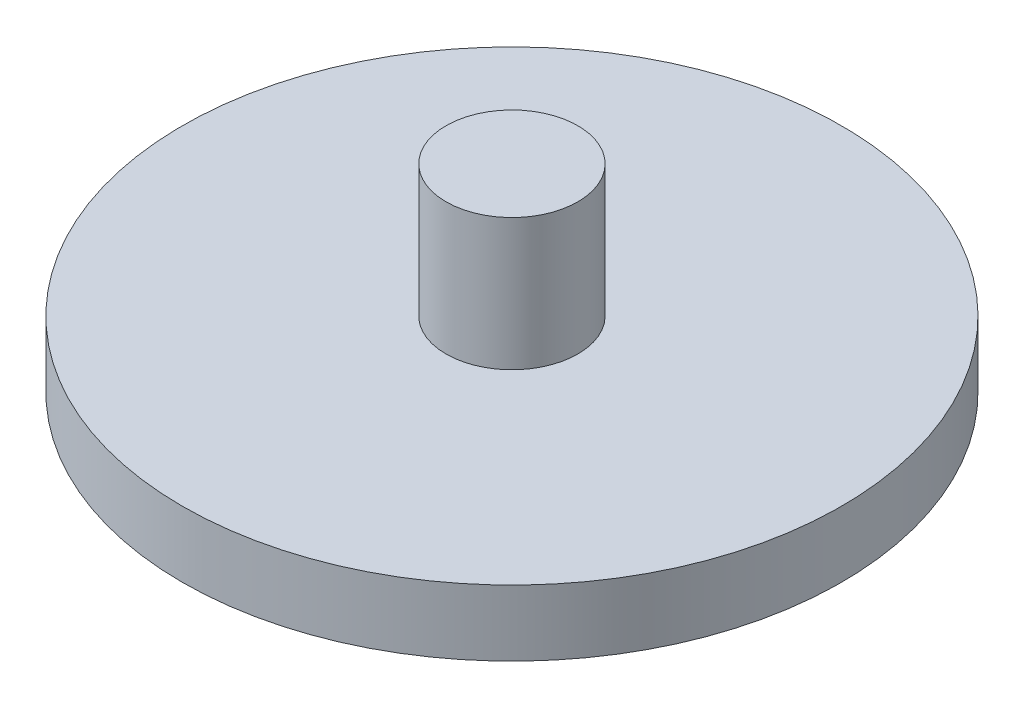
SolidWorks part; units mm, degrees
ref_plane "Front Plane" through (0, 0, 0) normal (0, 0, 1) x (1, 0, 0)
ref_plane "Top Plane" through (0, 0, 0) normal (0, 1, 0) x (1, 0, 0)
ref_plane "Right Plane" through (0, 0, 0) normal (1, 0, 0) x (0, 0, -1)
sketch "Sketch2" plane through (0, 0, 0) normal (0, 1, 0) x (1, 0, 0)
  circle A0 centre (0, 0) radius 50
  dimension "D1" = 100
extrude "Boss-Extrude1" add sketch "Sketch2" along normal blind 10
sketch "Sketch3" plane through (0, 10, 0) normal (0, 1, 0) x (1, 0, 0)
  circle A0 centre (0, 0) radius 10
  dimension "D1" = 20
extrude "Boss-Extrude2" add sketch "Sketch3" along normal blind 20
